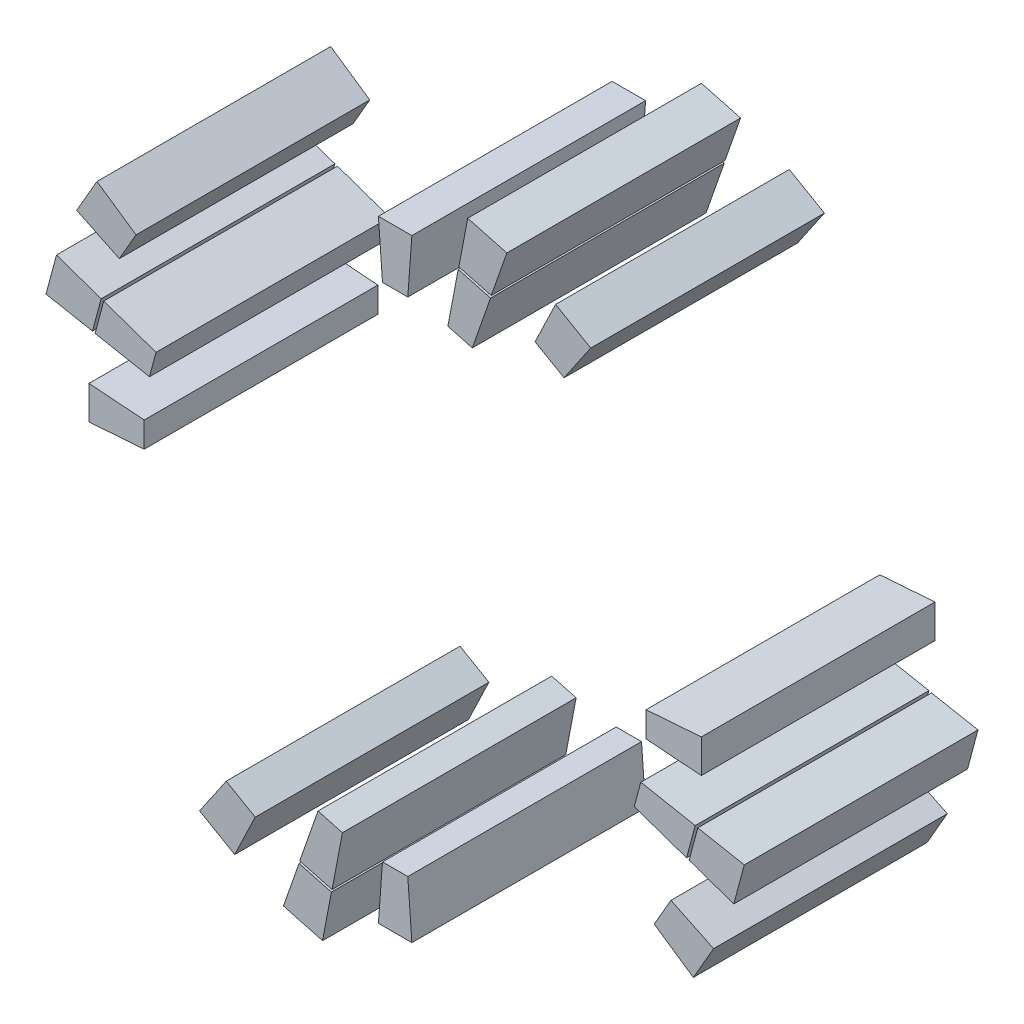
SolidWorks part; units mm, degrees
ref_plane "Спереди" through (0, 0, 0) normal (0, 0, 1) x (1, 0, 0)
ref_plane "Сверху" through (0, 0, 0) normal (0, 1, 0) x (1, 0, 0)
ref_plane "Справа" through (0, 0, 0) normal (1, 0, 0) x (0, 0, -1)
sketch "Эскиз1" plane through (0, 0, 0) normal (0, 0, 1) x (1, 0, 0)
  line L0 (32.209, -1.625) -> (39.3, -2.1473)
  line L1 (39.3, -2.1473) -> (39.3, 2.1473)
  line L2 (39.3, 2.1473) -> (32.209, 1.625)
  line L3 (32.209, 1.625) -> (32.209, -1.625)
  line L4 (21.6806, 33.2572) -> (25.1017, 38.2774)
  line L5 (25.1017, 38.2774) -> (20.5983, 40.8774)
  line L6 (20.5983, 40.8774) -> (17.9613, 35.4045)
  line L7 (17.9613, 35.4045) -> (21.6806, 33.2572)
  line L8 (9.9059, 30.691) -> (12.2457, 37.4051)
  line L9 (12.2457, 37.4051) -> (8.0974, 38.5167)
  line L10 (8.0974, 38.5167) -> (6.7667, 31.5321)
  line L11 (6.7667, 31.5321) -> (9.9059, 30.691)
  line L12 (12.3342, 37.7354) -> (14.3394, 43.4699)
  line L13 (14.3394, 43.4699) -> (9.3166, 44.8157)
  line L14 (9.3166, 44.8157) -> (8.1859, 38.8469)
  line L15 (8.1859, 38.8469) -> (12.3342, 37.7354)
  line L16 (1.625, 32.209) -> (2.1473, 39.3)
  line L17 (2.1473, 39.3) -> (-2.1473, 39.3)
  line L18 (-2.1473, 39.3) -> (-1.625, 32.209)
  line L19 (-1.625, 32.209) -> (1.625, 32.209)
  line L20 (-33.2572, 21.6806) -> (-38.2774, 25.1017)
  line L21 (-38.2774, 25.1017) -> (-40.8774, 20.5983)
  line L22 (-40.8774, 20.5983) -> (-35.4045, 17.9613)
  line L23 (-35.4045, 17.9613) -> (-33.2572, 21.6806)
  line L24 (-30.691, 9.9059) -> (-37.4051, 12.2457)
  line L25 (-37.4051, 12.2457) -> (-38.5167, 8.0974)
  line L26 (-38.5167, 8.0974) -> (-31.5321, 6.7667)
  line L27 (-31.5321, 6.7667) -> (-30.691, 9.9059)
  line L28 (-37.7354, 12.3342) -> (-43.4699, 14.3394)
  line L29 (-43.4699, 14.3394) -> (-44.8157, 9.3166)
  line L30 (-44.8157, 9.3166) -> (-38.8469, 8.1859)
  line L31 (-38.8469, 8.1859) -> (-37.7354, 12.3342)
  line L32 (-32.209, 1.625) -> (-39.3, 2.1473)
  line L33 (-39.3, 2.1473) -> (-39.3, -2.1473)
  line L34 (-39.3, -2.1473) -> (-32.209, -1.625)
  line L35 (-32.209, -1.625) -> (-32.209, 1.625)
  line L36 (-21.6806, -33.2572) -> (-25.1017, -38.2774)
  line L37 (-25.1017, -38.2774) -> (-20.5983, -40.8774)
  line L38 (-20.5983, -40.8774) -> (-17.9613, -35.4045)
  line L39 (-17.9613, -35.4045) -> (-21.6806, -33.2572)
  line L40 (-9.9059, -30.691) -> (-12.2457, -37.4051)
  line L41 (-12.2457, -37.4051) -> (-8.0974, -38.5167)
  line L42 (-8.0974, -38.5167) -> (-6.7667, -31.5321)
  line L43 (-6.7667, -31.5321) -> (-9.9059, -30.691)
  line L44 (-12.3342, -37.7354) -> (-14.3394, -43.4699)
  line L45 (-14.3394, -43.4699) -> (-9.3166, -44.8157)
  line L46 (-9.3166, -44.8157) -> (-8.1859, -38.8469)
  line L47 (-8.1859, -38.8469) -> (-12.3342, -37.7354)
  line L48 (-1.625, -32.209) -> (-2.1473, -39.3)
  line L49 (-2.1473, -39.3) -> (2.1473, -39.3)
  line L50 (2.1473, -39.3) -> (1.625, -32.209)
  line L51 (1.625, -32.209) -> (-1.625, -32.209)
  line L52 (33.2572, -21.6806) -> (38.2774, -25.1017)
  line L53 (38.2774, -25.1017) -> (40.8774, -20.5983)
  line L54 (40.8774, -20.5983) -> (35.4045, -17.9613)
  line L55 (35.4045, -17.9613) -> (33.2572, -21.6806)
  line L56 (30.691, -9.9059) -> (37.4051, -12.2457)
  line L57 (37.4051, -12.2457) -> (38.5167, -8.0974)
  line L58 (38.5167, -8.0974) -> (31.5321, -6.7667)
  line L59 (31.5321, -6.7667) -> (30.691, -9.9059)
  line L60 (37.7354, -12.3342) -> (43.4699, -14.3394)
  line L61 (43.4699, -14.3394) -> (44.8157, -9.3166)
  line L62 (44.8157, -9.3166) -> (38.8469, -8.1859)
  line L63 (38.8469, -8.1859) -> (37.7354, -12.3342)
extrude "Coil_sides" add sketch "Эскиз1" along normal blind 30 from offset 15 separate body
